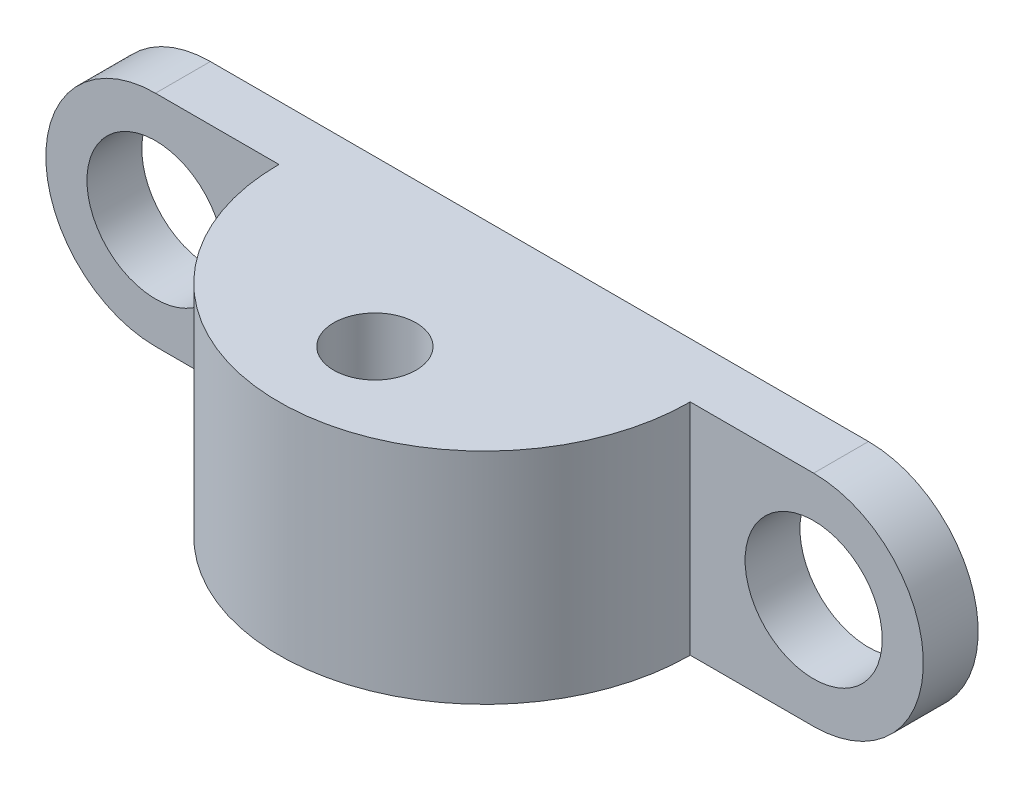
SolidWorks part; units mm, degrees
ref_plane "Front Plane" through (0, 0, 0) normal (0, 0, 1) x (1, 0, 0)
ref_plane "Top Plane" through (0, 0, 0) normal (0, 1, 0) x (1, 0, 0)
ref_plane "Right Plane" through (0, 0, 0) normal (1, 0, 0) x (0, 0, -1)
sketch "Sketch1" plane through (0, 0, 0) normal (0, 0, 1) x (1, 0, 0)
  line L1 (0, 4) -> (24, 4)
  line L2 (0, 4) -> (0, -4)
  line L3 (0, -4) -> (24, -4)
  line L4 (24, 4) -> (24, -4)
  circle A0 centre (0, 0) radius 4
  circle A1 centre (24, 0) radius 4
  dimension "D2" = 8
  dimension "D1" = 24
extrude "Boss-Extrude1" add sketch "Sketch1" along normal blind 2 contours L2 A0 | L2 A0 | A1 L1 A0 L3 | L4 A1 | L4 A1
sketch "Sketch2" plane through (0, -4, 0) normal (0, -1, 0) x (1, 0, 0)
  line L0 (0, 2) -> (24, 2) construction
  line L1 (7.5, 2) -> (16.5, 2)
  line L3 (4.5, 2) -> (19.5, 2)
  line L5 (0, 2) -> (24, 2) construction
  line L6 (7.5, 2) -> (16.5, 2) construction
  line L7 (0, 2) -> (7.5754, 2)
  line L8 (7.5754, 2) -> (22.4246, 2)
  line L9 (22.4246, 2) -> (24, 2)
  line L10 (12, 2) -> (12, 6) construction
  line L11 (0, 0) -> (24, 0) construction
  line L12 (12, 0) -> (12, 2) construction
  arc A0 (19.5, 2) -> (4.5, 2) centre (12, 2) ccw
  circle A1 centre (12, 6) radius 1.5
  point P12 (12, 2)
  point P13 (12, 2)
  dimension "D2" = 15
  dimension "D3" = 3
  dimension "D1" = 4
extrude "Boss-Extrude2" add sketch "Sketch2" against normal up to surface (8 mm away)
sketch "Sketch6" plane through (0, 0, 2) normal (0, 0, 1) x (1, 0, 0)
  line L3 (4.5, -4) -> (4.5, 4)
  line L4 (4.5, 4) -> (0, 4)
  line L5 (0, -4) -> (4.5, -4)
  line L7 (4.5, 4) -> (0, 4)
  line L8 (0, -4) -> (4.5, -4)
  line L9 (24, 4) -> (19.5, 4)
  line L10 (19.5, 4) -> (19.5, -4)
  line L11 (19.5, -4) -> (24, -4)
  line L12 (24, 4) -> (19.5, 4)
  line L14 (19.5, -4) -> (24, -4)
  line L15 (4.5, -4) -> (4.5, 4)
  line L16 (19.5, 4) -> (19.5, -4)
  circle A0 centre (0, 0) radius 2.5
  arc A1 (0, 4) -> (0, -4) centre (0, 0) ccw
  arc A2 (0, 4) -> (0, -4) centre (0, 0) ccw
  arc A3 (24, -4) -> (24, 4) centre (24, 0) ccw
  arc A4 (24, -4) -> (24, 4) centre (24, 0) ccw
  circle A5 centre (24, 0) radius 2.5
  dimension "D3" = 5
  dimension "D1" = 0
  dimension "D2" = 0
extrude "Cut-Extrude1" cut sketch "Sketch6" against normal through all contours A0 | A5
